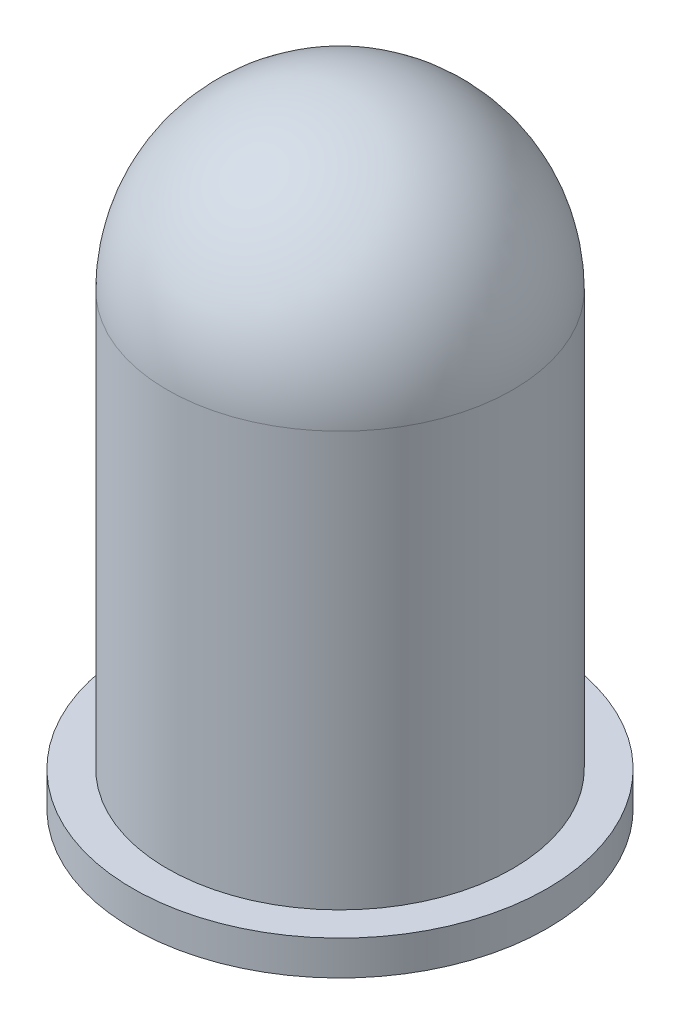
SolidWorks part; units mm, degrees
ref_plane "Front Plane" through (0, 0, 0) normal (0, 0, 1) x (1, 0, 0)
ref_plane "Top Plane" through (0, 0, 0) normal (0, 1, 0) x (1, 0, 0)
ref_plane "Right Plane" through (0, 0, 0) normal (1, 0, 0) x (0, 0, -1)
sketch "Sketch1" plane through (0, 0, 0) normal (0, 0, 1) x (1, 0, 0)
  line L0 (0, -624.0285) -> (0, 30577.3964) construction
  line L1 (0, 0) -> (-3, 0)
  line L2 (-3, 0) -> (-3, 0.5)
  line L3 (-3, 0.5) -> (-2.5, 0.5)
  line L4 (-2.5, 0.5) -> (-2.5, 6.5)
  line L5 (0, 9) -> (0, 0)
  arc A0 (-2.5, 6.5) -> (0, 9) centre (0, 6.5) cw
  point P10 (-2.5, 6.4299)
  point P11 (0, 0)
  dimension "D1" = 2.5
  dimension "D2" = 9
  dimension "D3" = 0.5
  dimension "D4" = 0.5
revolve "Revolve1" add sketch "Sketch1" angle 360 about L0
